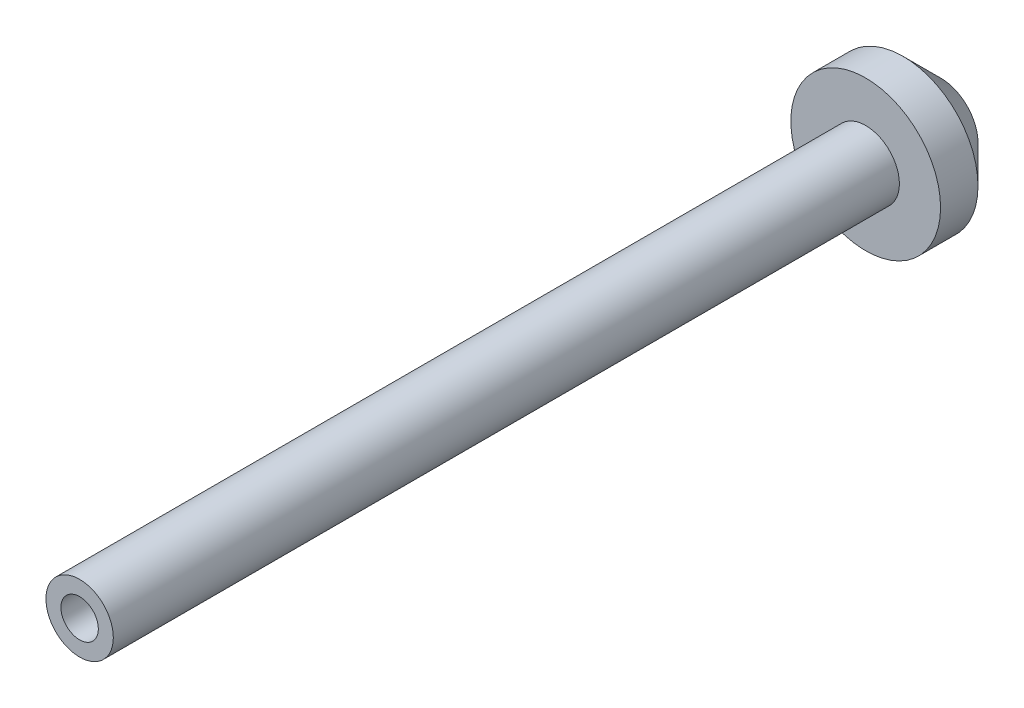
SolidWorks part; units mm, degrees
ref_plane "Front Plane" through (0, 0, 0) normal (0, 0, 1) x (1, 0, 0)
ref_plane "Top Plane" through (0, 0, 0) normal (0, 1, 0) x (1, 0, 0)
ref_plane "Right Plane" through (0, 0, 0) normal (1, 0, 0) x (0, 0, -1)
sketch "Sketch1" plane through (0, 0, 0) normal (0, 0, 1) x (1, 0, 0)
  circle A0 centre (0, 0) radius 5
  dimension "D1" = 10
extrude "Boss-Extrude1" add sketch "Sketch1" along normal blind 5
sketch "Sketch2" plane through (0, 0, 5) normal (0, 0, 1) x (1, 0, 0)
  circle A0 centre (0, 0) radius 2.25
  dimension "D1" = 4.5
extrude "Boss-Extrude2" add sketch "Sketch2" along normal blind 52.5
sketch "Sketch3" plane through (0, 0, 57.5) normal (0, 0, 1) x (1, 0, 0)
  circle A0 centre (0, 0) radius 1.25
  dimension "D1" = 2.5
extrude "Cut-Extrude1" cut sketch "Sketch3" against normal blind 10
chamfer "Chamfer1" distance 2.5 angle 45 1 edges at (5, 0, 0)
